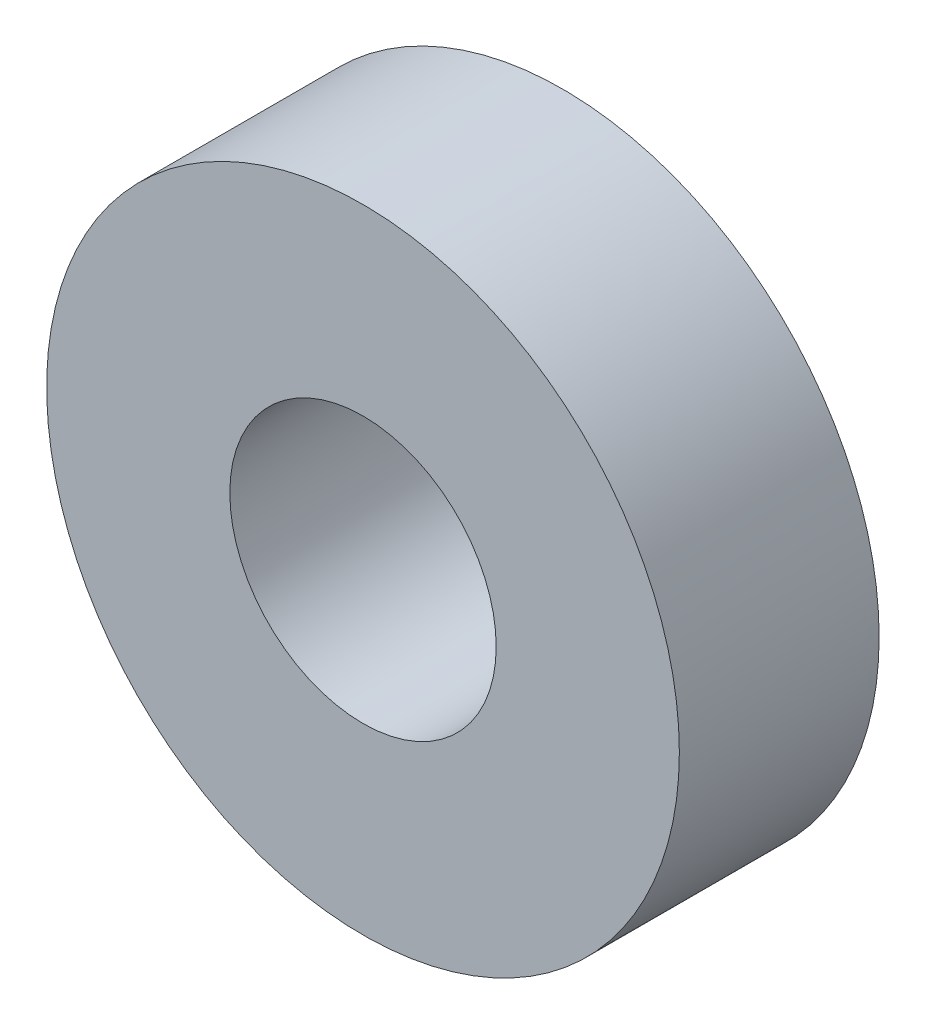
SolidWorks part; units mm, degrees
ref_plane "Alzado" through (0, 0, 0) normal (0, 0, 1) x (1, 0, 0)
ref_plane "Planta" through (0, 0, 0) normal (0, 1, 0) x (1, 0, 0)
ref_plane "Vista lateral" through (0, 0, 0) normal (1, 0, 0) x (0, 0, -1)
sketch "Model" plane through (0, 0, 0) normal (0, 0, 1) x (1, 0, 0)
  circle A0 centre (13.8138, 292.2514) radius 4.75
  circle A1 centre (13.8138, 292.2514) radius 2
extrude "Saliente-Extruir1" add sketch "Model" along normal blind 3
